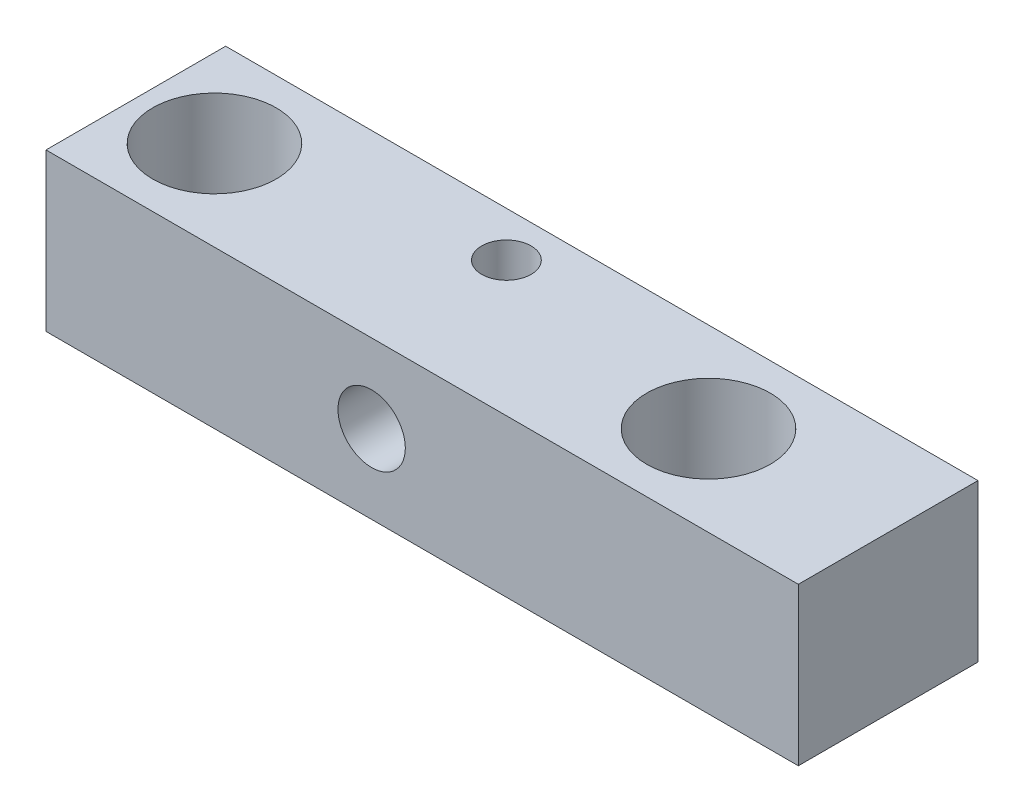
SolidWorks part; units mm, degrees
ref_plane "前视基准面" through (0, 0, 0) normal (0, 0, 1) x (1, 0, 0)
ref_plane "上视基准面" through (0, 0, 0) normal (0, 1, 0) x (1, 0, 0)
ref_plane "右视基准面" through (0, 0, 0) normal (1, 0, 0) x (0, 0, -1)
sketch "草图1" plane through (0, 0, 0) normal (0, 1, 0) x (1, 0, 0)
  line L0 (-13.5972, 4.2393) -> (24.4028, 4.2393) construction
  line L1 (-13.5972, 8.2393) -> (24.4028, 8.2393)
  line L2 (-13.5972, 8.2393) -> (-13.5972, 0.2393)
  line L3 (-13.5972, 0.2393) -> (24.4028, 0.2393)
  line L4 (24.4028, 8.2393) -> (24.4028, 0.2393)
  line L5 (-13.5972, 8.2393) -> (24.4028, 0.2393) construction
  line L6 (-13.5972, 0.2393) -> (24.4028, 8.2393) construction
  circle A0 centre (-5.5972, 4.2393) radius 2.75
  circle A1 centre (16.4028, 4.2393) radius 2.75
  circle A2 centre (5.4028, 6.2393) radius 1.1
  point P4 (5.4028, 4.2393)
  dimension "D3" = 5.5
  dimension "D4" = 5.5
  dimension "D7" = 2.2
  dimension "D1" = 38
  dimension "D2" = 8
  dimension "D5" = 8
  dimension "D6" = 8
  dimension "D8" = 2
extrude "凸台-拉伸1" add sketch "草图1" along normal blind 7
sketch "草图2" plane through (0, 0, -0.2393) normal (0, 0, 1) x (1, 0, 0)
  line L0 (-13.5972, 0) -> (24.4028, 0) construction
  line L1 (-13.5972, 7) -> (-9.0972, 7)
  line L2 (-13.5972, 7) -> (-13.5972, 0)
  line L3 (-13.5972, 0) -> (-9.0972, 0)
  line L4 (-9.0972, 7) -> (-9.0972, 0)
  line L5 (-13.5972, 7) -> (-9.0972, 0) construction
  line L6 (-13.5972, 0) -> (-9.0972, 7) construction
  point P4 (-11.3472, 3.5)
  dimension "D1" = 4.5
extrude "切除-拉伸1" cut sketch "草图2" against normal through all
sketch "草图4" plane through (0, 0, -0.2393) normal (0, 0, 1) x (1, 0, 0)
  line L0 (5.4028, 7) -> (5.4028, 0) construction
  line L1 (6.5028, 7) -> (4.3028, 7) construction
  line L2 (-9.0972, 0) -> (24.4028, 0) construction
  circle A0 centre (5.4028, 3.5) radius 1.5
  dimension "D1" = 3
extrude "切除-拉伸2" cut sketch "草图4" against normal blind 6
